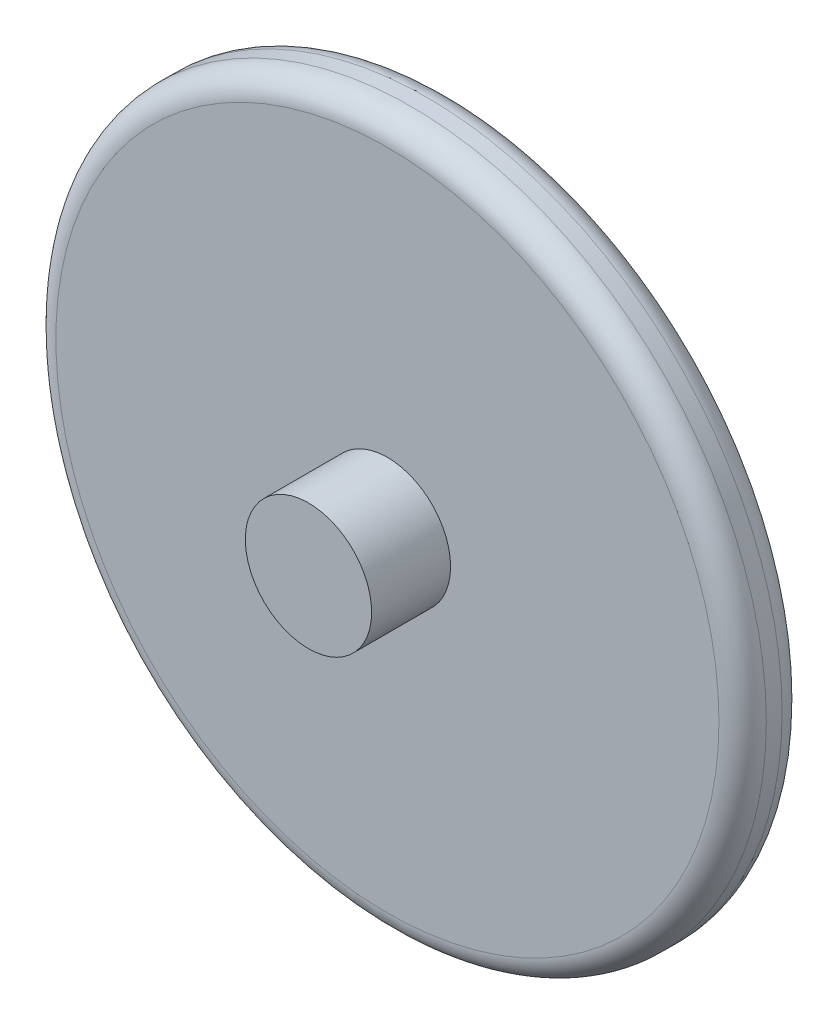
SolidWorks part; units mm, degrees
ref_plane "Alzado" through (0, 0, 0) normal (0, 0, 1) x (1, 0, 0)
ref_plane "Planta" through (0, 0, 0) normal (0, 1, 0) x (1, 0, 0)
ref_plane "Vista lateral" through (0, 0, 0) normal (1, 0, 0) x (0, 0, -1)
sketch "Croquis1" plane through (0, 0, 0) normal (0, 0, 1) x (1, 0, 0)
  circle A0 centre (0, 0) radius 45
  dimension "D1" = 90
extrude "Saliente-Extruir1" add sketch "Croquis1" along normal blind 8
sketch "Croquis2" plane through (0, 0, 8) normal (0, 0, 1) x (1, 0, 0)
  circle A0 centre (0, 0) radius 8
extrude "Saliente-Extruir2" add sketch "Croquis2" along normal blind 10
fillet "Redondeo1" radius 3 2 edges at (45, 0, 0) (45, 0, 8)
